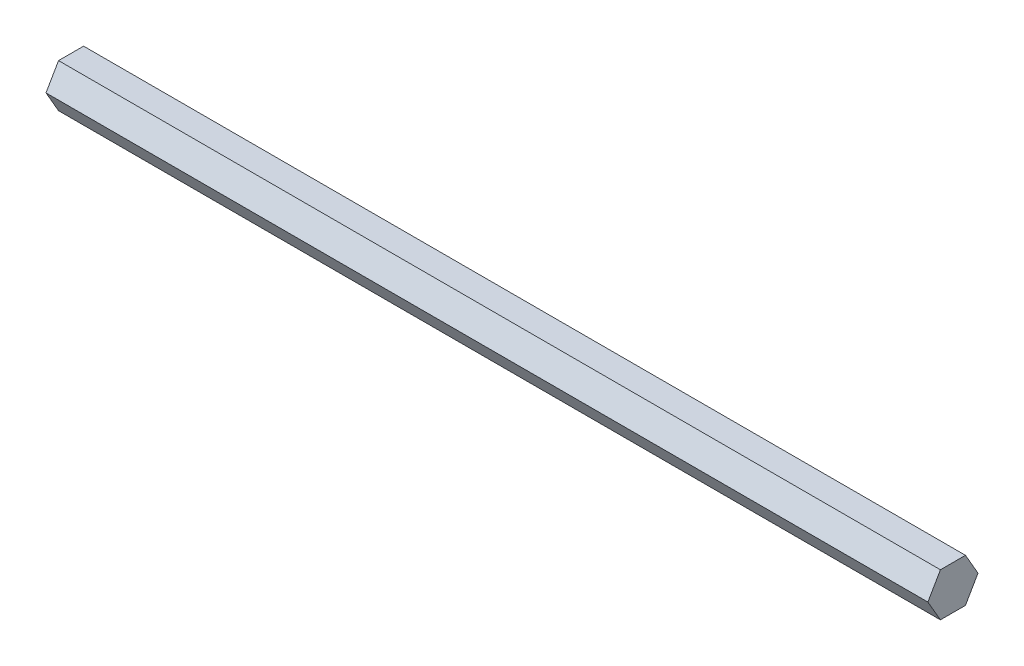
SolidWorks part; units mm, degrees
material "6061-T6 (SS)"
ref_plane "Front" through (0, 0, 0) normal (0, 0, 1) x (1, 0, 0)
ref_plane "Top" through (0, 0, 0) normal (0, 1, 0) x (1, 0, 0)
ref_plane "Right" through (0, 0, 0) normal (1, 0, 0) x (0, 0, -1)
sketch "Sketch1" plane through (0, 0, 0) normal (1, 0, 0) x (0, 0, -1)
  line L1 (1.4434, 2.5) -> (-1.4434, 2.5)
  line L2 (-1.4434, 2.5) -> (-2.8868, 0)
  line L3 (-2.8868, 0) -> (-1.4434, -2.5)
  line L4 (-1.4434, -2.5) -> (1.4434, -2.5)
  line L5 (1.4434, -2.5) -> (2.8868, 0)
  line L6 (2.8868, 0) -> (1.4434, 2.5)
  circle A0 centre (0, 0) radius 2.5 construction
  dimension "D1" = 5
extrude "Boss-Extrude1" add sketch "Sketch1" along normal blind 101.6
